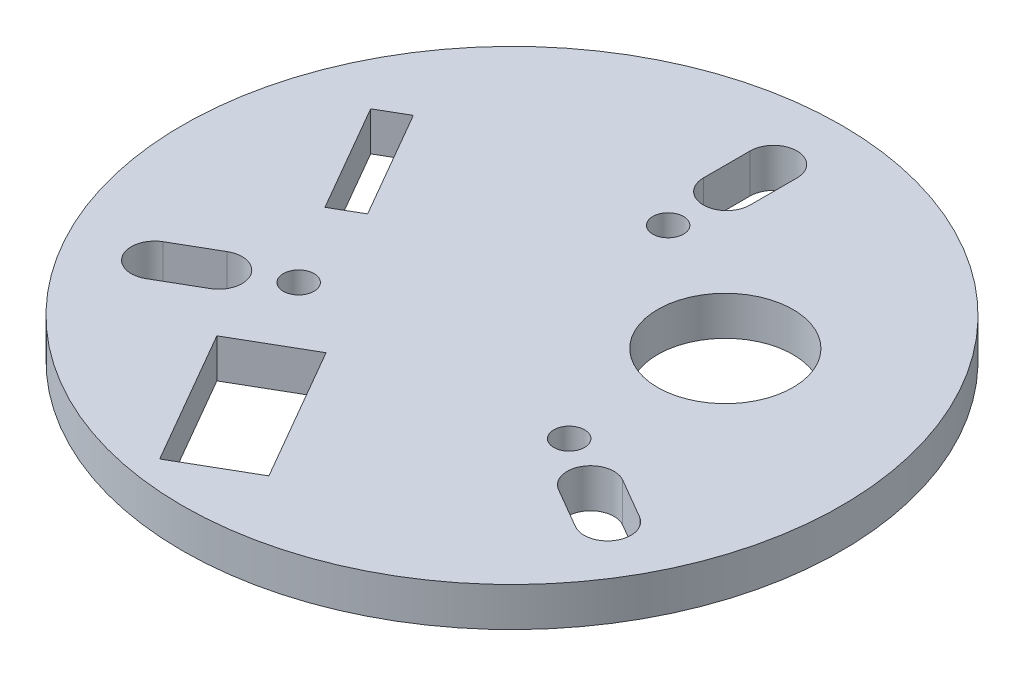
SolidWorks part; units mm, degrees
ref_plane "Front Plane" through (0, 0, 0) normal (0, 0, 1) x (1, 0, 0)
ref_plane "Top Plane" through (0, 0, 0) normal (0, 1, 0) x (1, 0, 0)
ref_plane "Right Plane" through (0, 0, 0) normal (1, 0, 0) x (0, 0, -1)
sketch "Sketch2" plane through (0, 0, 0) normal (0, 1, 0) x (1, 0, 0)
  circle A0 centre (0, 0) radius 26.8
  dimension "D1" = 53.6
extrude "Boss-Extrude1" add sketch "Sketch2" along normal blind 3.175
sketch "Sketch3" plane through (0, 3.175, 0) normal (0, 1, 0) x (1, 0, 0)
  line L0 (0, 0) -> (0, 26.8) construction
  line L1 (0, 0) -> (23.2095, -13.4) construction
  line L2 (0, 0) -> (-23.2095, -13.4) construction
  line L3 (-1.905, 21.2725) -> (-1.905, 17.4625)
  line L4 (-1.905, 21.2725) -> (1.905, 21.2725)
  line L5 (-1.905, 17.4625) -> (1.905, 17.4625)
  line L6 (1.905, 21.2725) -> (1.905, 17.4625)
  line L7 (-1.905, 21.2725) -> (1.905, 17.4625) construction
  line L8 (-1.905, 17.4625) -> (1.905, 21.2725) construction
  line L9 (-14.1704, -10.3811) -> (-17.47, -12.2861)
  line L10 (-14.1704, -10.3811) -> (-16.0754, -7.0816)
  line L11 (-17.47, -12.2861) -> (-19.375, -8.9866)
  line L12 (-16.0754, -7.0816) -> (-19.375, -8.9866)
  line L13 (-14.1704, -10.3811) -> (-19.375, -8.9866) construction
  line L14 (-17.47, -12.2861) -> (-16.0754, -7.0816) construction
  line L15 (14.1651, -10.3779) -> (17.4582, -12.2939)
  line L16 (14.1651, -10.3779) -> (16.0811, -7.0847)
  line L17 (17.4582, -12.2939) -> (19.3742, -9.0007)
  line L18 (16.0811, -7.0847) -> (19.3742, -9.0007)
  line L19 (14.1651, -10.3779) -> (19.3742, -9.0007) construction
  line L20 (17.4582, -12.2939) -> (16.0811, -7.0847) construction
  circle A0 centre (0, 0) radius 26.8 construction
  arc A1 (-1.905, 21.2725) -> (1.905, 21.2725) centre (0, 21.2725) cw
  arc A2 (-1.905, 17.4625) -> (1.905, 17.4625) centre (0, 17.4625) ccw
  arc A3 (17.4582, -12.2939) -> (19.3742, -9.0007) centre (18.4162, -10.6473) ccw
  arc A4 (14.1651, -10.3779) -> (16.0811, -7.0847) centre (15.1231, -8.7313) cw
  arc A5 (-14.1704, -10.3811) -> (-16.0754, -7.0816) centre (-15.1229, -8.7314) ccw
  arc A6 (-19.375, -8.9866) -> (-17.47, -12.2861) centre (-18.4225, -10.6364) ccw
  circle A7 centre (0, 12.7) radius 1.25
  circle A8 centre (-10.9985, -6.35) radius 1.25
  circle A9 centre (10.9985, -6.35) radius 1.25
  point P9 (0, 19.3675)
  point P10 (-16.7727, -9.6839)
  point P11 (16.7696, -9.6893)
  dimension "D16" = 12.7
  dimension "D17" = 2.5
  dimension "D19" = 12.7
  dimension "D1" = 120
  dimension "D2" = 120
  dimension "D3" = 17.4625
  dimension "D4" = 3.81
  dimension "D5" = 3.81
  dimension "D6" = 0.0001
  dimension "D7" = 3.81
  dimension "D8" = 3.81
  dimension "D9" = 17.4625
  dimension "D10" = 0.0001
  dimension "D11" = 3.81
  dimension "D12" = 0.0127
  dimension "D13" = 3.81
  dimension "D14" = 17.4625
  dimension "D15" = 1.905
  dimension "D18" = 12.7
extrude "Cut-Extrude1" cut sketch "Sketch3" against normal blind 3.175 contours L6 L4 L3 L5 | A1 L4 | L5 A2 | L18 L16 L15 L17 | A4 L16 | L17 A3 | L10 L12 L11 L9 | L10 A5 | L11 A6 | A8 | A7 | A9
sketch "Sketch4" plane through (0, 3.175, 0) normal (0, 1, 0) x (1, 0, 0)
  line L0 (0, 0) -> (19.9698, 11.5296) construction
  line L1 (1.905, 21.2725) -> (1.905, 17.4625) construction
  circle A1 centre (10.9985, 6.35) radius 5.5
  dimension "D4" = 12.7
  dimension "D5" = 11
  dimension "D3" = 60
extrude "Cut-Extrude2" cut sketch "Sketch4" against normal blind 7.62
sketch "Sketch5" plane through (0, 3.175, 0) normal (0, 1, 0) x (1, 0, 0)
  line L0 (6.2153, -21.8802) -> (-15.4264, 15.6042) construction
  line L1 (-14.1704, -10.3811) -> (-17.47, -12.2861) construction
  line L2 (-4.813, -2.7788) -> (-24.2081, -13.9766) construction
  line L3 (-4.2167, -24.4315) -> (1.4125, -21.1815)
  line L4 (-4.2167, -24.4315) -> (-10.5667, -13.433)
  line L5 (1.4125, -21.1815) -> (-4.9375, -10.183)
  line L6 (-10.5667, -13.433) -> (-4.9375, -10.183)
  line L7 (-15.2221, 0.0104) -> (-13.0224, 1.2804)
  line L8 (-15.2221, 0.0104) -> (-20.3021, 8.8092)
  line L9 (-13.0224, 1.2804) -> (-18.1024, 10.0792)
  line L10 (-20.3021, 8.8092) -> (-18.1024, 10.0792)
  circle A0 centre (-10.9985, -6.35) radius 1.25 construction
  point P9 (-1.7625, -15.6823)
  dimension "D1" = 5.5575
  dimension "D2" = 90
  dimension "D3" = 0
  dimension "D4" = 7.62
  dimension "D5" = 6.5
  dimension "D6" = 12.7
  dimension "D7" = 19.05
  dimension "D8" = 17.78
  dimension "D9" = 10.16
  dimension "D10" = 2.54
  dimension "D11" = 10.16
extrude "Cut-Extrude3" cut sketch "Sketch5" against normal blind 5.08
